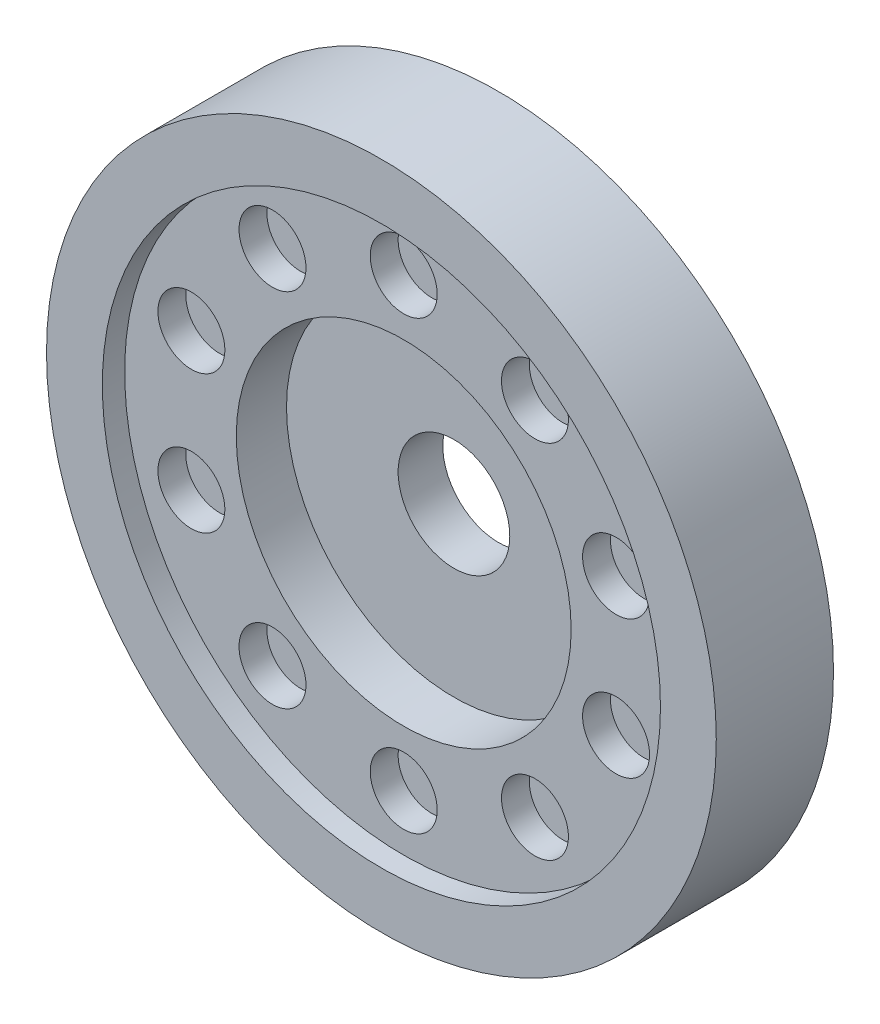
SolidWorks part; units mm, degrees
ref_plane "Front Plane" through (0, 0, 0) normal (0, 0, 1) x (1, 0, 0)
ref_plane "Top Plane" through (0, 0, 0) normal (0, 1, 0) x (1, 0, 0)
ref_plane "Right Plane" through (0, 0, 0) normal (1, 0, 0) x (0, 0, -1)
sketch "Sketch1" plane through (0, 0, 0) normal (0, 0, 1) x (1, 0, 0)
  circle A0 centre (0, 0) radius 381
extrude "Boss-Extrude1" add sketch "Sketch1" along normal blind 133.35
sketch "Sketch2" plane through (0, 0, 133.35) normal (0, 0, 1) x (1, 0, 0)
  circle A0 centre (0, 0) radius 63.5
extrude "Cut-Extrude1" cut sketch "Sketch2" against normal through all
sketch "Sketch6" plane through (0, 0, 133.35) normal (0, 0, 1) x (1, 0, 0)
  circle A0 centre (0, 0) radius 317.5
extrude "Cut-Extrude5" cut sketch "Sketch6" against normal blind 25.4
sketch "Sketch7" plane through (0, 0, 133.35) normal (0, 0, 1) x (1, 0, 0)
  circle A0 centre (0, 0) radius 190.5
extrude "Cut-Extrude6" cut sketch "Sketch7" against normal blind 82.55
sketch "Sketch8" plane through (0, 0, 133.35) normal (0, 0, 1) x (1, 0, 0)
  line L0 (0, 0) -> (0, 418.6344) construction
  circle A0 centre (0, 0) radius 254 construction
  circle A1 centre (0, 254) radius 38.1
  circle A2 centre (149.2975, 205.4903) radius 38.1
  circle A3 centre (241.5684, 78.4903) radius 38.1
  circle A4 centre (241.5684, -78.4903) radius 38.1
  circle A5 centre (149.2975, -205.4903) radius 38.1
  circle A6 centre (0, -254) radius 38.1
  circle A7 centre (-149.2975, -205.4903) radius 38.1
  circle A8 centre (-241.5684, -78.4903) radius 38.1
  circle A9 centre (-241.5684, 78.4903) radius 38.1
  circle A10 centre (-149.2975, 205.4903) radius 38.1
  point P26 (0, 0)
  dimension "D1" = 10
extrude "Cut-Extrude8" cut sketch "Sketch8" against normal blind 57.15
